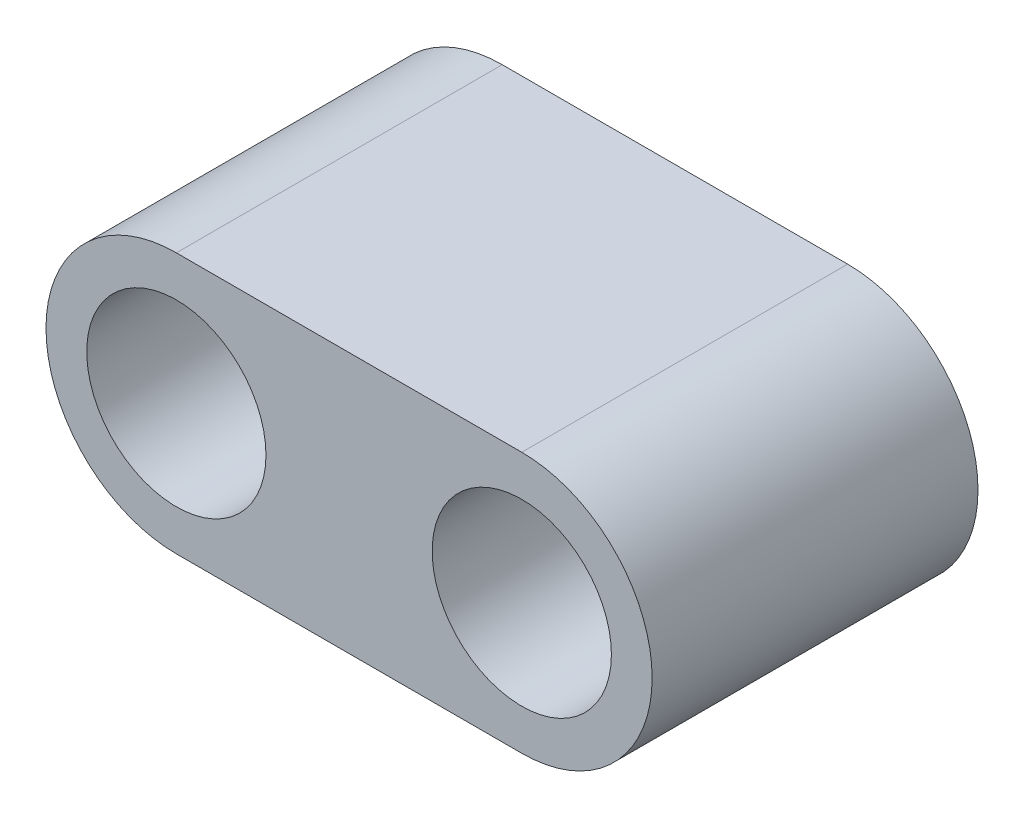
SolidWorks part; units mm, degrees
ref_plane "Front Plane" through (0, 0, 0) normal (0, 0, 1) x (1, 0, 0)
ref_plane "Top Plane" through (0, 0, 0) normal (0, 1, 0) x (1, 0, 0)
ref_plane "Right Plane" through (0, 0, 0) normal (1, 0, 0) x (0, 0, -1)
sketch "Sketch1" plane through (0, 0, 0) normal (0, 0, 1) x (1, 0, 0)
  line L0 (0, 0) -> (106, 0)
  line L1 (0, -80) -> (106, -80)
  arc A1 (0, 0) -> (0, -80) centre (0, -40) ccw
  arc A2 (106, 0) -> (106, -80) centre (106, -40) cw
  dimension "D1" = 40
  dimension "D2" = 106
extrude "Boss-Extrude1" add sketch "Sketch1" along normal blind 100
sketch "Sketch2" plane through (0, 0, 100) normal (0, 0, 1) x (1, 0, 0)
  line L0 (0, 0) -> (0, -80) construction
  line L1 (106, 0) -> (106, -80) construction
  line L2 (106, -40) -> (0, -40) construction
  circle A0 centre (0, -40) radius 27.5
  circle A1 centre (106, -40) radius 27.5
  dimension "D1" = 55
extrude "Cut-Extrude1" cut sketch "Sketch2" against normal through all
